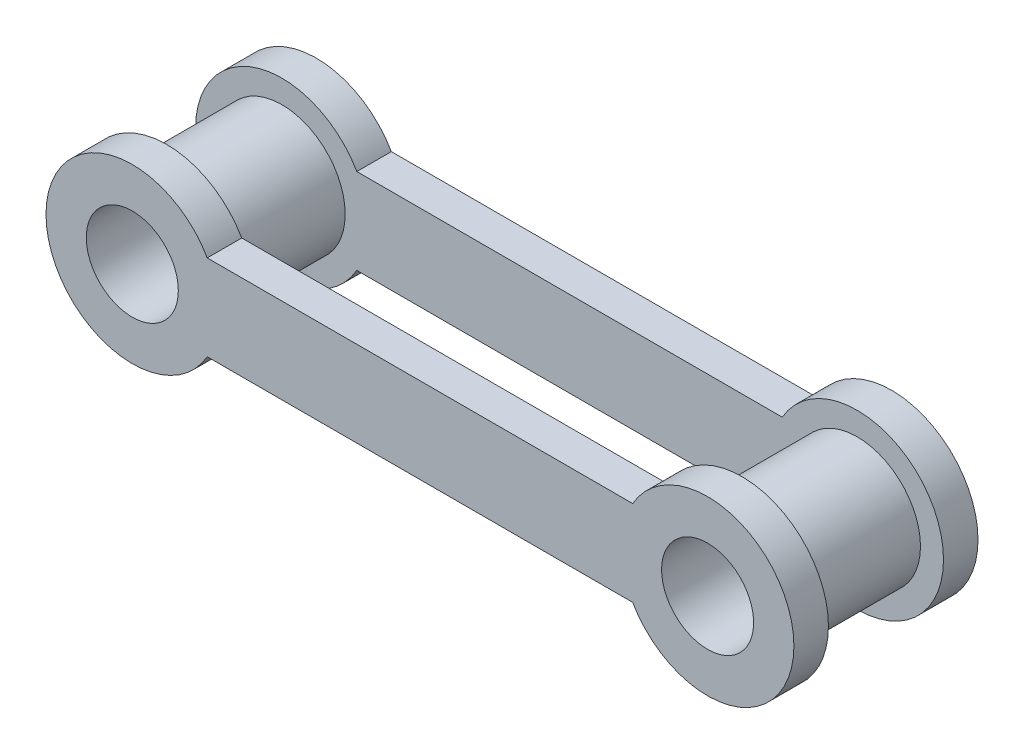
SolidWorks part; units mm, degrees
ref_plane "前视基准面" through (0, 0, 0) normal (0, 0, 1) x (1, 0, 0)
ref_plane "上视基准面" through (0, 0, 0) normal (0, 1, 0) x (1, 0, 0)
ref_plane "右视基准面" through (0, 0, 0) normal (1, 0, 0) x (0, 0, -1)
sketch "草图1" plane through (0, 0, 0) normal (0, 0, 1) x (1, 0, 0)
  line L0 (11.9608, 1.7358) -> (11.9608, 2.5566) construction
  line L1 (11.9608, 2.5566) -> (11.9608, 1.0742) construction
  line L2 (11.9608, 1.7358) -> (-4.1648, 1.7358) construction
  line L3 (-4.1648, 1.7358) -> (-1.5737, 1.7358) construction
  line L4 (-6.5266, 5.4554) -> (30.4481, 5.4554)
  line L5 (-6.5266, -1.9838) -> (30.4481, -1.9838)
  arc A0 (-6.5266, 5.4554) -> (-6.5266, -1.9838) centre (-13.0392, 1.7358) ccw
  circle A1 centre (-13.0392, 1.7358) radius 4
  circle A2 centre (36.9608, 1.7358) radius 4
  arc A3 (30.4481, 5.4554) -> (30.4481, -1.9838) centre (36.9608, 1.7358) cw
  dimension "D2" = 15
  dimension "D3" = 8
  dimension "D1" = 25
extrude "凸台-拉伸1" add sketch "草图1" along normal blind 3
sketch "草图2" plane through (0, 0, 3) normal (0, 0, 1) x (1, 0, 0)
  circle A0 centre (-13.0392, 1.7358) radius 5.5
  circle A1 centre (36.9608, 1.7358) radius 5.5
  circle A2 centre (36.9608, 1.7358) radius 4 construction
  circle A3 centre (-13.0392, 1.7358) radius 4 construction
  circle A4 centre (36.9608, 1.7358) radius 4
  circle A5 centre (-13.0392, 1.7358) radius 4
extrude "凸台-拉伸2" add sketch "草图2" along normal blind 10
ref_plane "基准面1" through (0, 0, 8) normal (0, 0, 1) x (1, 0, 0)
mirror "镜向1" about plane through (0, 0, 8) normal (0, 0, 1) of "凸台-拉伸1"
